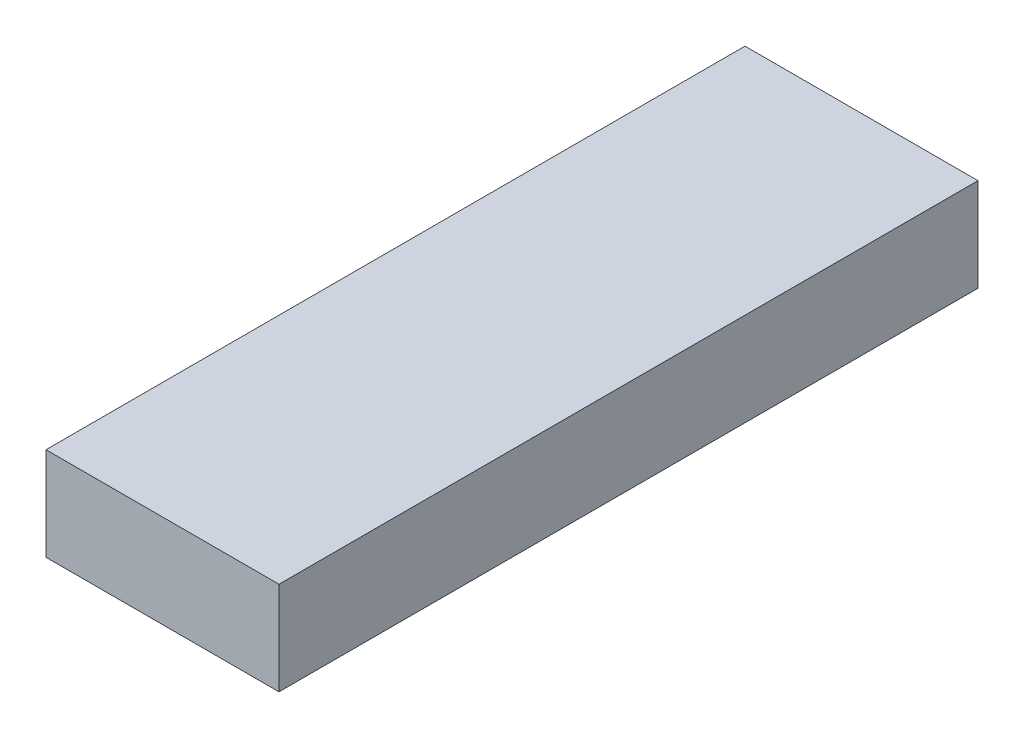
SolidWorks part; units mm, degrees
ref_plane "Front Plane" through (0, 0, 0) normal (0, 0, 1) x (1, 0, 0)
ref_plane "Top Plane" through (0, 0, 0) normal (0, 1, 0) x (1, 0, 0)
ref_plane "Right Plane" through (0, 0, 0) normal (1, 0, 0) x (0, 0, -1)
sketch "Sketch1" plane through (0, 0, 0) normal (0, 0, 1) x (1, 0, 0)
  line L1 (-5, -2) -> (5, -2)
  line L2 (-5, -2) -> (-5, 2)
  line L3 (-5, 2) -> (5, 2)
  line L4 (5, -2) -> (5, 2)
  line L5 (-5, -2) -> (5, 2) construction
  line L6 (-5, 2) -> (5, -2) construction
  point P0 (0, 0)
  dimension "D1" = 4
  dimension "D2" = 10
extrude "Boss-Extrude1" add sketch "Sketch1" along normal blind 30
